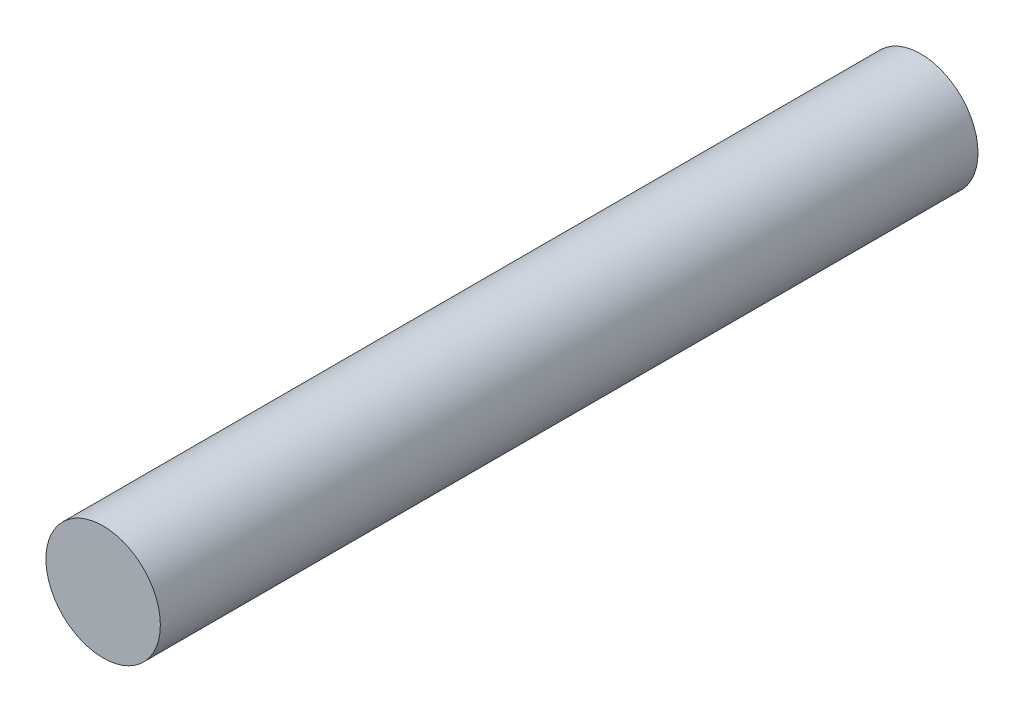
SolidWorks part; units mm, degrees
ref_plane "前视基准面" through (0, 0, 0) normal (0, 0, 1) x (1, 0, 0)
ref_plane "上视基准面" through (0, 0, 0) normal (0, 1, 0) x (1, 0, 0)
ref_plane "右视基准面" through (0, 0, 0) normal (1, 0, 0) x (0, 0, -1)
sketch "草图1" plane through (0, 0, 0) normal (0, 0, 1) x (1, 0, 0)
  circle A0 centre (0, 0) radius 1.75
  dimension "D1" = 3.5
extrude "凸台-拉伸1" add sketch "草图1" along normal blind 25
cosmetic thread "装饰螺纹线1" parameters "D2"=2.013
cosmetic thread "装饰螺纹线2" parameters "D2"=2.459
